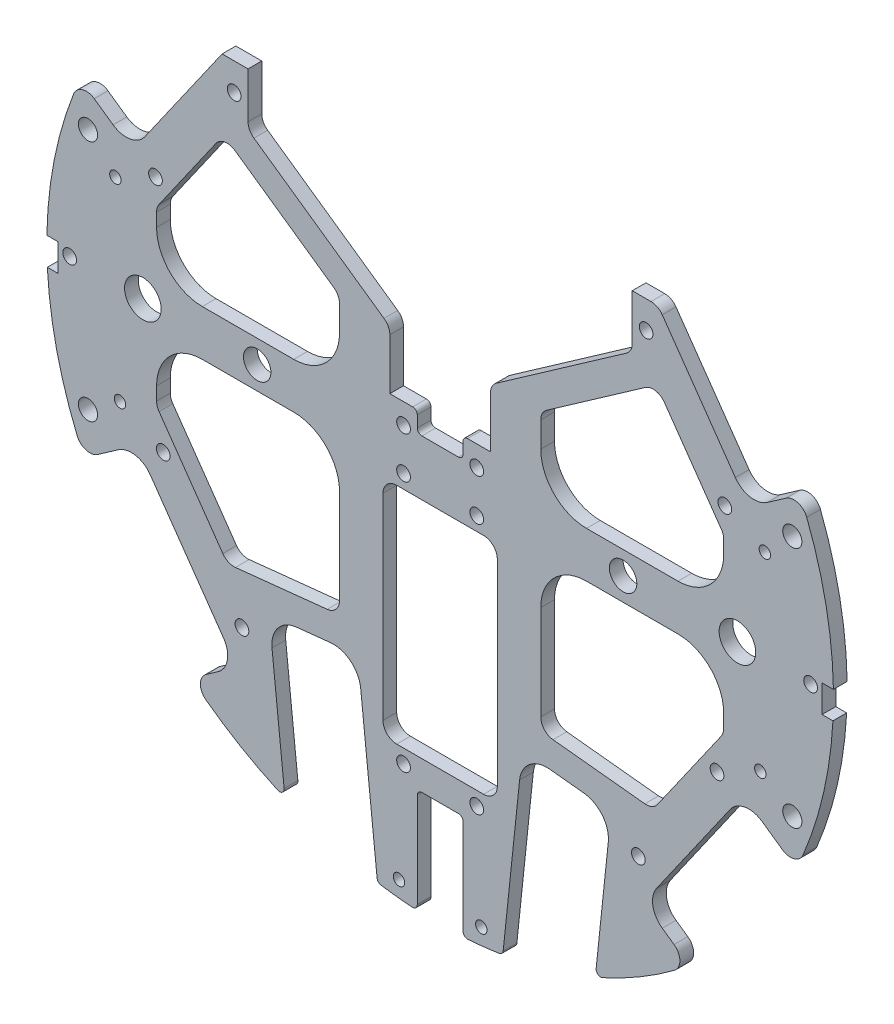
SolidWorks part; units mm, degrees
material "2A12"
ref_plane "前视基准面" through (0, 0, 0) normal (0, 0, 1) x (1, 0, 0)
ref_plane "上视基准面" through (0, 0, 0) normal (0, 1, 0) x (1, 0, 0)
ref_plane "右视基准面" through (0, 0, 0) normal (1, 0, 0) x (0, 0, -1)
sketch "草图1" plane through (0, 0, 0) normal (0, 0, 1) x (1, 0, 0)
  circle A0 centre (0, 0) radius 86
  dimension "D1" = 172
extrude "拉伸1" add sketch "草图1" along normal blind 3
sketch "草图15" plane through (0, 0, 0) normal (0, 0, -1) x (-1, 0, 0)
  line L1 (0, 4) -> (-50.9559, 39.6797) construction
  line L3 (0, 86) -> (0, -86) construction
  line L4 (0, 0) -> (-86, 0) construction
  line L5 (0, -4) -> (-50.5463, -39.3929) construction
  circle A0 centre (0, 0) radius 86 construction
  circle A2 centre (0, 0) radius 64.5 construction
  dimension "D2" = 129
  dimension "D5" = 4
  dimension "D6" = 55
  dimension "D8" = 4
  dimension "D10" = 55
sketch "草图21" plane through (0, 0, 0) normal (0, 0, -1) x (-1, 0, 0)
  line L0 (-47.6683, 55) -> (-42, 55)
  line L1 (0, 0) -> (0, 55) construction
  line L2 (-47.6683, 55) -> (-67.4196, 26.7922)
  line L3 (47.6683, 55) -> (67.4196, 26.7922)
  line L5 (42, 55) -> (42, 51)
  line L6 (-67.4196, 26.7922) -> (-78.6944, 34.687)
  line L7 (67.4196, 26.7922) -> (78.6944, 34.687)
  line L8 (20, 39) -> (-20, 39)
  line L9 (-42, 51) -> (-42, 55)
  line L10 (42, 51) -> (37.0711, 46.0711) construction
  line L11 (42, 55) -> (47.6683, 55)
  line L12 (0, 4) -> (-50.9559, 39.6797) construction
  line L13 (-37.0711, 46.0711) -> (-42, 51) construction
  line L14 (-20, 39) -> (-37.0711, 46.0711) construction
  line L15 (37.0711, 46.0711) -> (20, 39) construction
  line L16 (42, 51) -> (42, 31.5079) construction
  line L17 (20, 39) -> (47.6223, 39) construction
  line L18 (20, 39) -> (42, 39)
  line L19 (42, 39) -> (42, 51)
  line L20 (-42, 51) -> (-42, 39)
  line L21 (-20, 39) -> (-42, 39)
  circle A0 centre (0, 0) radius 86 construction
  arc A1 (78.6944, 34.687) -> (-78.6944, 34.687) centre (0, 0) ccw
  point P13 (-42, 39)
  point P16 (-42, 39)
  point P17 (42, 39)
  point P20 (42, 39)
  point P22 (30, 39)
  point P23 (42, 39)
  point P25 (-30, 39)
  point P26 (-41.5, 39)
  dimension "D4" = 39
  dimension "D1" = 55
  dimension "D2" = 68.3
  dimension "D3" = 20
  dimension "D5" = 84
extrude "拉伸2" cut sketch "草图21" against normal blind 10
sketch "草图31" plane through (0, 0, 0) normal (0, 0, -1) x (-1, 0, 0)
  line L1 (-11, 39) -> (11, 39)
  line L2 (-11, 39) -> (-11, 9)
  line L3 (-11, 9) -> (11, 9)
  line L4 (11, 39) -> (11, 9)
  line L5 (0, 0) -> (0, 39) construction
  line L6 (-42, 39) -> (42, 39) construction
  dimension "D1" = 22
  dimension "D2" = 30
extrude "拉伸5" cut sketch "草图31" against normal blind 10
sketch "草图22" plane through (0, 0, 0) normal (0, 0, -1) x (-1, 0, 0)
  line L0 (-77.852, -36.5386) -> (-66.2725, -28.4305)
  line L1 (-66.2725, -28.4305) -> (-44.4766, -59.5583)
  line L2 (-44.4766, -59.5583) -> (-54.4668, -66.5535)
  line L5 (0, -4) -> (-50.5463, -39.3929) construction
  circle A0 centre (0, 0) radius 86 construction
  arc A1 (-77.852, -36.5386) -> (-54.4668, -66.5535) centre (0, 0) ccw
  dimension "D1" = 38
  dimension "D2" = 18
  dimension "D3" = 68.3
extrude "拉伸3" cut sketch "草图22" against normal blind 10
mirror "镜向7" about plane through (0, 0, 0) normal (1, 0, 0) of "拉伸3"
sketch "草图27" plane through (0, 0, 0) normal (0, 0, -1) x (-1, 0, 0)
  line L0 (-12.5, -32.1) -> (12.5, -32.1) construction
  line L1 (-12.5, -7.6) -> (12.5, -7.6)
  line L2 (-12.5, -7.6) -> (-12.5, -56.6)
  line L3 (-12.5, -56.6) -> (12.5, -56.6)
  line L4 (12.5, -7.6) -> (12.5, -56.6)
  line L5 (0, 0) -> (0, -32.1) construction
  dimension "D1" = 25
  dimension "D2" = 49
  dimension "D3" = 56.6
extrude "拉伸4" cut sketch "草图27" against normal blind 10
fillet "圆角1" radius 3 11 edges at (12.5, -56.6, 1.5) (-12.5, -56.6, 1.5) (-12.5, -7.6, 1.5) (12.5, -7.6, 1.5) (78.6944, 34.687, 1.5) (77.852, -36.5386, 1.5) (54.4668, -66.5535, 1.5) (-54.4668, -66.5535, 1.5) (-77.852, -36.5386, 1.5) (-78.6944, 34.687, 1.5) (47.6683, 55, 1.5)
sketch "草图28" plane through (0, 0, 0) normal (0, 0, -1) x (-1, 0, 0)
  line L0 (-8, -32.1) -> (8, -32.1) construction
  line L1 (-8, -4.6) -> (8, -4.6)
  line L2 (-8, -4.6) -> (-8, -59.6)
  line L3 (-8, -59.6) -> (8, -59.6)
  line L4 (8, -4.6) -> (8, -59.6)
  line L5 (0, -56.6) -> (0, -32.1) construction
  line L6 (-9.5, -56.6) -> (9.5, -56.6) construction
  line L7 (-12.5, -32.1) -> (-8, -32.1) construction
  line L8 (-12.5, -10.6) -> (-12.5, -53.6) construction
  dimension "D1" = 55
  dimension "D2" = 16
hole_wizard "打孔尺寸根据内六角圆柱头螺钉的类型6" [suppressed] positions "3D草图6" profile "草图29" counterbore size "M3" standard "GB"
sketch3d "3D草图6"
  point P0 (8, -17.5, 0)
  point P3 (-8, -17.5, 0)
  point P18 (8, -60.5, 0)
  point P21 (-8, -60.5, 0)
sketch "草图29" plane through (8, -17.5, 0) normal (1, 0, 0) x (0, 1, 0)
  line L0 (0, 0) -> (0, 3)
  line L1 (0, 3) -> (1.7, 3)
  line L3 (1.7, 3) -> (1.7, 1.8)
  line L4 (1.7, 1.8) -> (3, 1.8)
  line L5 (3, 1.8) -> (3, 0)
  line L7 (3, 0) -> (0, 0)
  line L11 (0, -6.35) -> (0, 107.95) construction
  dimension "通孔孔直径" = 3.4
  dimension "通孔孔深度" = 3
  dimension "柱形沉头孔直径" = 6
  dimension "柱形沉头孔深度" = 1.8
sketch "草图33" plane through (0, 0, 3) normal (0, 0, 1) x (1, 0, 0)
  line L0 (0, 0) -> (0, -63) construction
  line L1 (4, -63) -> (-4, -63)
  line L2 (4, -63) -> (4, -88)
  line L3 (4, -88) -> (-4, -88)
  line L4 (-4, -63) -> (-4, -88)
  dimension "D1" = 8
  dimension "D2" = 63
  dimension "D3" = 25
extrude "拉伸8" cut sketch "草图33" against normal blind 10
fillet "圆角3" [suppressed] radius 1
fillet "圆角4" [suppressed] radius 3
sketch "草图34" plane through (0, 0, 0) normal (0, 0, -1) x (-1, 0, 0)
  line L0 (-13.7011, -84.9016) -> (-18, -44)
  line L1 (-18, -44) -> (-37.3932, -46.0383)
  line L2 (-37.3932, -46.0383) -> (-33.9261, -79.0254)
  line L3 (-4, -85.9069) -> (-4, -63) construction
  arc A0 (-51.2072, -69.0929) -> (-4, -85.9069) centre (0, 0) ccw construction
  arc A1 (-33.9261, -79.0254) -> (-13.7011, -84.9016) centre (0, 0) ccw
  dimension "D1" = 6
  dimension "D2" = 44
  dimension "D3" = 18
  dimension "D4" = 19.5
extrude "拉伸9" cut sketch "草图34" against normal blind 10
fillet "圆角5" radius 6 2 edges at (18, -44, 1.5) (37.3932, -46.0383, 1.5)
mirror "镜向10" about plane through (0, 0, 0) normal (1, 0, 0) of "圆角5", "拉伸9"
sketch "草图35" plane through (0, 0, 0) normal (0, 0, -1) x (-1, 0, 0)
  line L0 (0, 0) -> (0, 29) construction
  line L1 (-14, 29) -> (14, 29) construction
  line L2 (-14, 29) -> (-14, 35) construction
  line L3 (-14, 35) -> (14, 35) construction
  line L4 (14, 29) -> (14, 35) construction
  circle A0 centre (-14, 35) radius 1.75
  circle A1 centre (-14, 29) radius 1.75
  circle A2 centre (14, 29) radius 1.75
  circle A3 centre (14, 35) radius 1.75
  dimension "D4" = 3.5
  dimension "D1" = 29
  dimension "D2" = 6
  dimension "D3" = 28
extrude "拉伸10" [suppressed] cut sketch "草图35" against normal blind 10
fillet "圆角6" [suppressed] radius 1
fillet "圆角7" radius 1 4 edges at (-13.7011, -84.9016, 1.5) (13.7011, -84.9016, 1.5) (-4, -85.9069, 1.5) (4, -85.9069, 1.5)
sketch "草图37" plane through (0, 0, 0) normal (0, 0, -1) x (-1, 0, 0)
  line L0 (-8, 4.5) -> (8, 4.5) construction
  line L1 (0, 9) -> (0, 4.5) construction
  line L2 (-11, 9) -> (11, 9) construction
  circle A0 centre (-8, 4.5) radius 1.5
  circle A1 centre (8, 4.5) radius 1.5
  dimension "D3" = 3
  dimension "D1" = 16
  dimension "D2" = 4.5
extrude "拉伸12" cut sketch "草图37" against normal blind 20
sketch "草图38" plane through (0, 0, 0) normal (0, 0, -1) x (-1, 0, 0)
  line L0 (-74.5, 2.75) -> (-74.5, -14.25) construction
  line L1 (0, 0) -> (-74.5, 0) construction
  circle A0 centre (-74.5, 2.75) radius 1.25
  circle A1 centre (-74.5, -14.25) radius 1.25
  dimension "D3" = 2.5
  dimension "D1" = 17
  dimension "D2" = 74.5
  dimension "D4" = 2.75
extrude "拉伸13" [suppressed] cut sketch "草图38" against normal blind 10
cosmetic thread "装饰螺纹线1" [suppressed] parameters "D1"=3, "D2"=3
cosmetic thread "装饰螺纹线2" [suppressed] parameters "D1"=3, "D2"=3
sketch "草图39" plane through (0, 0, 0) normal (0, 0, -1) x (-1, 0, 0)
  circle A0 centre (-8, -4.6) radius 1.5
  circle A1 centre (8, -4.6) radius 1.5
  circle A2 centre (-8, -59.6) radius 1.5
  circle A3 centre (8, -59.6) radius 1.5
  dimension "D1" = 3
extrude "拉伸14" cut sketch "草图39" against normal blind 10
mirror "镜向11" [suppressed] about plane through (0, 0, 0) normal (1, 0, 0)
sketch "草图41" plane through (0, 0, 0) normal (0, 0, -1) x (-1, 0, 0)
  line L0 (0, 0) -> (0, -15.6) construction
  line L1 (-18.5, -15.6) -> (18.5, -15.6)
  line L2 (-18.5, -15.6) -> (-18.5, -23.6)
  line L3 (-18.5, -23.6) -> (18.5, -23.6)
  line L4 (18.5, -15.6) -> (18.5, -23.6)
  line L5 (9.5, -7.6) -> (-9.5, -7.6) construction
  dimension "D1" = 37
  dimension "D2" = 8
  dimension "D3" = 8
extrude "拉伸16" [suppressed] cut sketch "草图41" against normal blind 5
fillet "圆角8" [suppressed] radius 1
sketch "草图42" plane through (0, 0, 0) normal (0, 0, -1) x (-1, 0, 0)
  line L0 (-77, -27) -> (77, -27) construction
  line L1 (0, 0) -> (0, -27) construction
  circle A0 centre (-77, -27) radius 1
  circle A1 centre (77, -27) radius 1
  dimension "D3" = 2
  dimension "D1" = 27
  dimension "D2" = 154
extrude "拉伸17" cut sketch "草图42" against normal blind 10
fillet "圆角10" radius 5 6 edges at (-67.4196, 26.7922, 1.5) (-66.2725, -28.4305, 1.5) (-44.4766, -59.5583, 1.5) (44.4766, -59.5583, 1.5) (66.2725, -28.4305, 1.5) (67.4196, 26.7922, 1.5)
chamfer "倒角1" [suppressed] distance 0.5 angle 45
chamfer "倒角2" [suppressed] distance 0.5 angle 45
sketch "草图43" plane through (0, 0, 3) normal (0, 0, 1) x (1, 0, 0)
  line L1 (-89.5, 1.5) -> (-83.5, 1.5)
  line L2 (-89.5, 1.5) -> (-89.5, -4.5)
  line L3 (-89.5, -4.5) -> (-83.5, -4.5)
  line L4 (-83.5, 1.5) -> (-83.5, -4.5)
  line L5 (-42, 39) -> (-11, 39) construction
  dimension "D1" = 83.5
  dimension "D2" = 6
  dimension "D3" = 37.5
  dimension "D4" = 6
extrude "拉伸18" cut sketch "草图43" against normal blind 10
sketch "Sketch4" plane through (0, 0, 0) normal (0, 0, -1) x (-1, 0, 0)
  line L0 (-11, 9) -> (11, 9) construction
  line L1 (-5, 9) -> (5, 9)
  line L2 (-5, 9) -> (-5, 4.5)
  line L3 (-5, 4.5) -> (5, 4.5)
  line L4 (5, 9) -> (5, 4.5)
  line L5 (0, 0) -> (0, 4.5) construction
  line L6 (0, 86) -> (0, -86) construction
  dimension "D1" = 10
  dimension "D2" = 4.5
extrude "Extrude2" cut sketch "Sketch4" against normal blind 10
fillet "Fillet1" radius 1 4 edges at (-5, 9, 1.5) (-5, 4.5, 1.5) (5, 4.5, 1.5) (5, 9, 1.5)
sketch "Sketch5" plane through (0, 0, 0) normal (0, 0, -1) x (-1, 0, 0)
  line L0 (-4, -84.8528) -> (-4, -63) construction
  line L1 (4, -63) -> (4, -84.8528) construction
  line L2 (-4, -64) -> (4, -64) construction
  line L3 (-4, -63) -> (-4, -65)
  arc A0 (-4, -63) -> (-4, -65) centre (-4, -64) ccw
  circle A1 centre (4, -64) radius 1
  dimension "D1" = 1
  dimension "D2" = 2
extrude "Extrude3" cut sketch "Sketch5" against normal blind 10
sketch "草图45" plane through (0, 0, 3) normal (0, 0, 1) x (1, 0, 0)
  line L0 (-4, -65) -> (-5.0588, -85.8511)
extrude "切除-拉伸1" cut sketch "草图45" against normal through all and the other way through all
mirror "镜向14" about plane through (0, 0, 0) normal (1, 0, 0) of "切除-拉伸1"
sketch "草图49" plane through (0, 0, 0) normal (0, 0, -1) x (-1, 0, 0)
  line L0 (-62, 5) -> (-22, 5)
  line L2 (-22, 22.102) -> (-22, 5)
  line L4 (-47.3084, 39.8231) -> (-62, 18.8412)
  line L5 (-62, 18.8412) -> (-62, 5)
  line L6 (-64.5517, 30.888) -> (-48.5641, 53.7207) construction
  line L7 (-42, 55) -> (-42, 39) construction
  line L8 (-11, 39) -> (-11, 9) construction
  line L12 (-22, 22.102) -> (-47.3084, 39.8231)
  dimension "D1" = 9
  dimension "D2" = 11
  dimension "D3" = 5.3084
  dimension "D4" = 5
  dimension "D5" = 40
extrude "切除-拉伸6" cut sketch "草图49" against normal blind 10
sketch "草图50" plane through (0, 0, 0) normal (0, 0, -1) x (-1, 0, 0)
  line L0 (-22, -5) -> (-22, -38.3874)
  line L1 (-46.5098, -40.9635) -> (-22, -38.3874)
  line L2 (-12.5, -10.6) -> (-12.5, -53.6) construction
  line L3 (-46.5098, -40.9635) -> (-62, -18.8412)
  line L4 (-62, -5) -> (-62, -18.8412)
  line L5 (-23.9671, -44.6272) -> (-31.426, -45.4111) construction
  line L6 (-62, -5) -> (-22, -5)
  line L7 (-47.3444, -55.4626) -> (-63.4046, -32.5263) construction
  line L8 (-62, 5) -> (-22, 5) construction
  dimension "D1" = 6
  dimension "D2" = 9
  dimension "D3" = 10
  dimension "D4" = 9.5
  dimension "D5" = 40
extrude "切除-拉伸7" cut sketch "草图50" against normal blind 10 contours L3 L4 L6 L0 L1
fillet "圆角23" radius 4 1 edges at (11, 39, 1.5)
mirror "镜向16" about plane through (0, 0, 0) normal (1, 0, 0) of "切除-拉伸7"
mirror "镜向17" about plane through (0, 0, 0) normal (1, 0, 0) of "切除-拉伸6"
fillet "圆角25" radius 4 1 edges at (-11, 39, 1.5)
sketch "草图51" plane through (0, 0, 0) normal (0, 0, -1) x (-1, 0, 0)
  line L0 (-64.5517, 30.888) -> (-48.5641, 53.7207) construction
  line L2 (-46.1066, 55) -> (-42, 55) construction
  line L3 (-45.0332, 49) -> (-62.2405, 24.4254) construction
  circle A0 centre (-45.0332, 49) radius 1.5
  circle A1 centre (-62.2405, 24.4254) radius 1.5
  dimension "D2" = 6
  dimension "D4" = 3
  dimension "D1" = 5.6
  dimension "D3" = 30
extrude "切除-拉伸8" cut sketch "草图51" against normal blind 10
sketch "草图52" plane through (0, 0, 0) normal (0, 0, -1) x (-1, 0, 0)
  line L0 (-43.3354, -51.4346) -> (-60.5427, -26.8601) construction
  line L1 (-46.5098, -40.9635) -> (-62, -18.8412) construction
  circle A0 centre (-43.3354, -51.4346) radius 1.5
  circle A1 centre (-60.5427, -26.8601) radius 1.5
  dimension "D3" = 3
  dimension "D5" = 3
  dimension "D1" = 51.4346
  dimension "D2" = 43.3354
  dimension "D4" = 30
extrude "切除-拉伸9" cut sketch "草图52" against normal blind 10
sketch "草图53" plane through (0, 0, 0) normal (0, 0, -1) x (-1, 0, 0)
  line L1 (9, 82) -> (-9, 82)
  line L2 (9, 82) -> (9, -82)
  line L3 (9, -82) -> (-9, -82)
  line L4 (-9, 82) -> (-9, -82)
  line L5 (9, 82) -> (-9, -82) construction
  line L6 (9, -82) -> (-9, 82) construction
  point P0 (0, 0)
  dimension "D1" = 82
  dimension "D2" = 18
hole_wizard "M3 螺纹孔1" positions "3D草图7" profile "草图54" tap size "M3" standard "GB" end condition through all
sketch3d "3D草图7"
  point P0 (9, -82, 0)
  point P3 (-9, -82, 0)
sketch "草图54" plane through (9, -82, 0) normal (1, 0, 0) x (0, 1, 0)
  line L0 (0, 0) -> (0, 3)
  line L1 (0, 3) -> (1.25, 3)
  line L2 (1.25, 3) -> (1.25, 0)
  line L5 (1.25, 0) -> (0, 0)
  line L11 (0, -6.35) -> (0, 107.95) construction
  dimension "通孔螺纹孔钻头直径" = 2.5
  dimension "通孔螺纹孔钻头深度" = 3
cosmetic thread "孔螺蚊线1" parameters "D2"=3
cosmetic thread "孔螺蚊线2" parameters "D2"=3
mirror "镜向18" about plane through (0, 0, 0) normal (1, 0, 0) of "切除-拉伸9", "切除-拉伸8"
hole_wizard "M5 螺纹孔1" positions "草图56" profile "草图55" tap size "M5" standard "GB" end condition through all
sketch "草图56" plane through (0, 0, 0) normal (0, 0, -1) x (-1, 0, 0)
  point P0 (-77, -27)
  point P3 (77, -27)
sketch "草图55" plane through (77, -27, 0) normal (1, 0, 0) x (0, 1, 0)
  line L0 (0, 0) -> (0, 3)
  line L1 (0, 3) -> (2.1, 3)
  line L2 (2.1, 3) -> (2.1, 0)
  line L5 (2.1, 0) -> (0, 0)
  line L11 (0, -6.35) -> (0, 107.95) construction
  dimension "通孔螺纹孔钻头直径" = 4.2
  dimension "通孔螺纹孔钻头深度" = 3
cosmetic thread "孔螺蚊线3" parameters "D1"=0, "D2"=5.2
cosmetic thread "孔螺蚊线4" parameters "D1"=0, "D2"=5.2
sketch "草图57" plane through (0, 0, 0) normal (0, 0, -1) x (-1, 0, 0)
  line L0 (83.5, -1.5) -> (79.5, -1.5) construction
  line L1 (83.5, -4.5) -> (83.5, 1.5) construction
  circle A0 centre (79.5, -1.5) radius 1.6
  dimension "D1" = 3.2
  dimension "D2" = 4
extrude "切除-拉伸10" [suppressed] cut sketch "草图57" against normal blind 10
mirror "镜向19" about plane through (0, 0, 0) normal (1, 0, 0) of "拉伸18"
sketch "草图58" plane through (0, 0, 0) normal (0, 0, -1) x (-1, 0, 0)
  circle A0 centre (-77, 26) radius 2.1
  circle A1 centre (-77, 26) radius 4 construction
  dimension "D1" = 77
  dimension "D2" = 26
  dimension "D3" = 4.2
  dimension "D4" = 8
extrude "切除-拉伸11" cut sketch "草图58" against normal blind 10
cosmetic thread "孔螺蚊线5" parameters "D1"=3, "D2"=5
hole_wizard "M5 螺纹孔2" positions "3D草图8" profile "草图59" tap size "M5" standard "GB"
sketch3d "3D草图8"
  line L0 (77, 26, 3) -> (77, 26, 0) construction
  point P0 (77, 26, 0)
sketch "草图59" plane through (77, 26, 0) normal (1, 0, 0) x (0, 1, 0)
  line L0 (0, 0) -> (0, 13.6618)
  line L1 (0, 13.6618) -> (2.1, 12.4)
  line L2 (2.1, 12.4) -> (2.1, 0)
  line L5 (2.1, 0) -> (0, 0)
  line L10 (0, 13.6618) -> (-2.1, 12.4) construction
  line L11 (0, -6.35) -> (0, 107.95) construction
  dimension "螺纹孔钻头直径" = 4.2
  dimension "螺纹孔钻头深度" = 12.4
  dimension "导头角度" = 118
mirror "镜向20" about plane through (0, 0, 0) normal (1, 0, 0) of "切除-拉伸11"
fillet "圆角27" radius 1 2 edges at (-33.9261, -79.0254, 1.5) (33.9261, -79.0254, 1.5)
sketch "草图61" plane through (0, 0, 0) normal (0, 0, -1) x (-1, 0, 0)
  line L0 (-11, 21.7243) -> (-35.6722, 39)
  line L1 (-22, 22.102) -> (-47.3084, 39.8231) construction
  line L2 (-42, 39) -> (-15, 39) construction
  line L3 (-11, 35) -> (-11, 9) construction
  line L4 (-35.6722, 39) -> (-15, 39)
  line L5 (-11, 35) -> (-11, 21.7243)
  arc A0 (-11, 35) -> (-15, 39) centre (-15, 35) ccw construction
  arc A1 (-11, 35) -> (-15, 39) centre (-15, 35) ccw
  dimension "D1" = 6
extrude "切除-拉伸12" cut sketch "草图61" against normal blind 10
sketch "草图62" plane through (0, 0, 0) normal (0, 0, -1) x (-1, 0, 0)
  line L0 (-35.6722, 39) -> (-42, 43.4308)
  line L1 (-42, 55) -> (-42, 39) construction
  line L2 (-42, 43.4308) -> (-42, 39)
  line L3 (-42, 39) -> (-35.6722, 39)
  line L4 (-35.6722, 39) -> (-11, 21.7243) construction
extrude "凸台-拉伸1" add sketch "草图62" against normal blind 3
mirror "镜向21" about plane through (0, 0, 0) normal (1, 0, 0) of "切除-拉伸12"
sketch "草图63" plane through (0, 0, 0) normal (0, 0, -1) x (-1, 0, 0)
  line L0 (35.6722, 39) -> (42, 43.4308)
  line L1 (42, 39) -> (42, 55) construction
  line L2 (42, 43.4308) -> (42, 39)
  line L3 (42, 39) -> (35.6722, 39)
  line L4 (35.6722, 39) -> (11, 21.7243) construction
ref_plane "基准面1" through (-42, 39, 3) normal (0, -1, 0) x (-1, 0, 0)
extrude "凸台-拉伸2" add sketch "草图63" against normal blind 3 contours L0 L2 L3
fillet "圆角28" radius 3 16 edges at (-42, 43.4308, 1.5) (42, 43.4308, 1.5) (11, 21.7243, 1.5) (-11, 21.7243, 1.5) (-62, -18.8412, 1.5) (-46.5098, -40.9635, 1.5) (-22, -38.3874, 1.5) (62, -18.8412, 1.5) (22, -38.3874, 1.5) (46.5098, -40.9635, 1.5) (62, 18.8412, 1.5) (47.3084, 39.8231, 1.5) (22, 22.102, 1.5) (-22, 22.102, 1.5) (-62, 18.8412, 1.5) (-47.3084, 39.8231, 1.5)
sketch "草图64" plane through (0, 0, 0) normal (0, 0, -1) x (-1, 0, 0)
  line L0 (0, 0) -> (0, -1) construction
  line L1 (71, -20) -> (-71, -20)
  line L2 (71, -20) -> (71, 20)
  line L3 (71, 20) -> (-71, 20)
  line L4 (-71, -20) -> (-71, 20)
  line L5 (71, -20) -> (-71, 20) construction
  line L6 (71, 20) -> (-71, -20) construction
  line L8 (70, 20) -> (-70, 20)
  line L9 (70, 20) -> (70, -22)
  line L10 (70, -22) -> (-70, -22)
  line L11 (-70, 20) -> (-70, -22)
  line L12 (70, 20) -> (-70, -22) construction
  line L13 (70, -22) -> (-70, 20) construction
  arc A0 (-85.8822, -4.5) -> (-79.3554, -33.147) centre (0, 0) ccw construction
  point P0 (0, 0)
  point P5 (0, -1)
  dimension "D1" = 40
  dimension "D2" = 142
  dimension "D3" = 1
  dimension "D4" = 140
  dimension "D5" = 22
hole_wizard "M3 螺纹孔2" positions "3D草图9" profile "草图65" tap size "M3" standard "GB" end condition through all
sketch3d "3D草图9"
  point P0 (-71, 20, 0)
  point P3 (-70, -22, 0)
  point P6 (71, 20, 0)
  point P9 (70, -22, 0)
sketch "草图65" plane through (-71, 20, 0) normal (1, 0, 0) x (0, 1, 0)
  line L0 (0, 0) -> (0, 3)
  line L1 (0, 3) -> (1.25, 3)
  line L2 (1.25, 3) -> (1.25, 0)
  line L5 (1.25, 0) -> (0, 0)
  line L11 (0, -6.35) -> (0, 107.95) construction
  dimension "通孔螺纹孔钻头直径" = 2.5
  dimension "通孔螺纹孔钻头深度" = 3
cosmetic thread "孔螺蚊线6" parameters "D2"=3
cosmetic thread "孔螺蚊线7" parameters "D2"=3
cosmetic thread "孔螺蚊线8" parameters "D2"=3
cosmetic thread "孔螺蚊线9" parameters "D2"=3
sketch "草图67" plane through (0, 0, 0) normal (0, 0, -1) x (-1, 0, 0)
  circle A0 centre (-77, 26) radius 4 construction
  dimension "D1" = 8
hole_wizard "Ø3.0 (3) 直径孔1" positions "草图69" profile "草图68" hole size "Ø3.0" standard "GB" end condition through all
sketch "草图69" plane through (0, 0, 0) normal (0, 0, -1) x (-1, 0, 0)
  point P0 (81, 0)
  point P3 (-81, 0)
sketch "草图68" plane through (-81, 0, 0) normal (1, 0, 0) x (0, 1, 0)
  line L0 (0, 0) -> (0, 3)
  line L1 (0, 3) -> (1.5, 3)
  line L2 (1.5, 3) -> (1.5, 0)
  line L5 (1.5, 0) -> (0, 0)
  line L11 (0, -6.35) -> (0, 107.95) construction
  dimension "通孔孔直径" = 3
  dimension "通孔孔深度" = 3
sketch "草图71" plane through (0, 0, 0) normal (0, 0, -1) x (-1, 0, 0)
  line L0 (-5, -64) -> (-5, -99.8401)
  line L1 (-5, -64) -> (5, -64)
  line L2 (5, -64) -> (5, -99.8401)
  line L3 (5, -99.8401) -> (-5, -99.8401)
  arc A0 (-4, -63) -> (-4, -65) centre (-4, -64) ccw construction
  arc A1 (4, -65) -> (4, -63) centre (4, -64) ccw construction
extrude "切除-拉伸13" cut sketch "草图71" against normal up to surface (3 mm away) up to face at (-82.5, 0, 3)
fillet "圆角21" radius 1 2 edges at (5.0588, -85.8511, 1.5) (-5.0588, -85.8511, 1.5)
sketch "草图72" plane through (0, 0, 0) normal (0, 0, -1) x (-1, 0, 0)
  line L0 (-62, 5) -> (-22, 5) construction
  line L1 (62, 5) -> (22, 5) construction
  circle A0 centre (-40, 0) radius 3
  circle A1 centre (-65, 0) radius 4
  circle A2 centre (40, 0) radius 3
  circle A3 centre (65, 0) radius 4
  dimension "D1" = 40
  dimension "D2" = 40
  dimension "D3" = 25
  dimension "D4" = 25
  dimension "D5" = 5
  dimension "D6" = 5
  dimension "D7" = 5
  dimension "D8" = 8
  dimension "D9" = 6
  dimension "D10" = 6
  dimension "D11" = 8
  dimension "D12" = 5
extrude "切除-拉伸14" cut sketch "草图72" against normal through all
fillet "圆角29" radius 10 8 edges at (-62, 5, 1.5) (-62, -5, 1.5) (-22, -5, 1.5) (-22, 5, 1.5) (22, -5, 1.5) (22, 5, 1.5) (62, -5, 1.5) (62, 5, 1.5)
